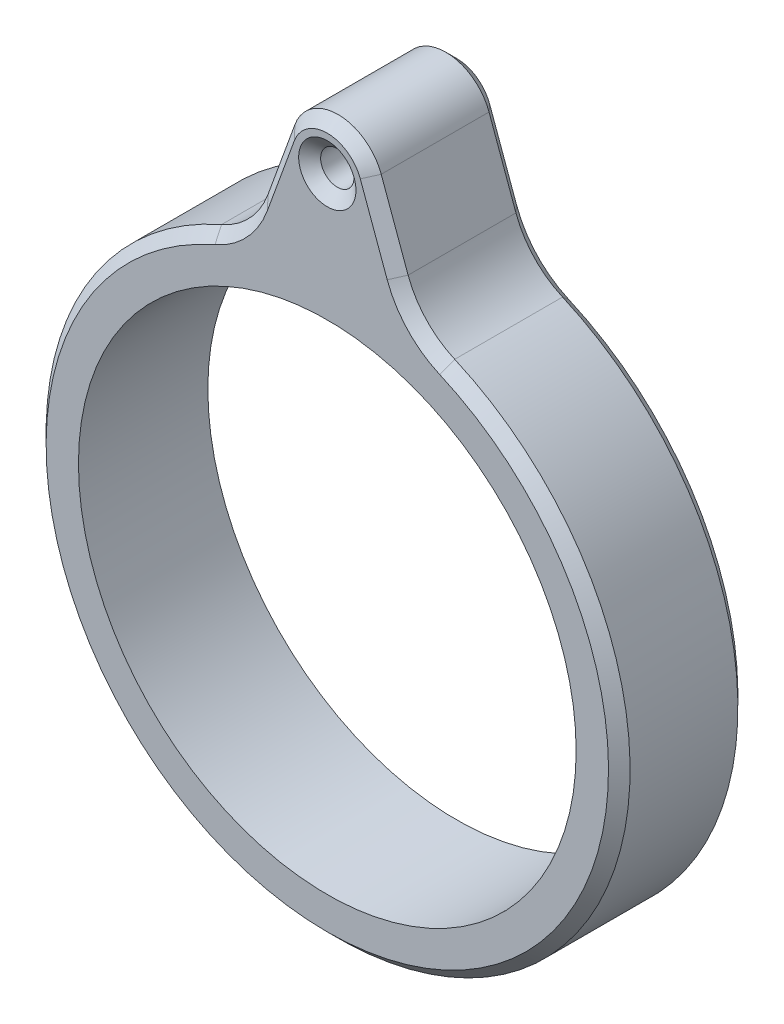
SolidWorks part; units mm, degrees
material "PET"
ref_plane "Front Plane" through (0, 0, 0) normal (0, 0, 1) x (1, 0, 0)
ref_plane "Top Plane" through (0, 0, 0) normal (0, 1, 0) x (1, 0, 0)
ref_plane "Right Plane" through (0, 0, 0) normal (1, 0, 0) x (0, 0, -1)
sketch "Sketch1" plane through (0, 0, 0) normal (0, 0, 1) x (1, 0, 0)
  circle A0 centre (0, 0) radius 36.6395
  circle A1 centre (0, 0) radius 42.9895
  dimension "D1" = 73.279
  dimension "D2" = 6.35
extrude "Boss-Extrude1" add sketch "Sketch1" along normal blind 19.05
sketch "Sketch3" plane through (0, 0, 19.05) normal (0, 0, 1) x (1, 0, 0)
  line L0 (0, 42.9895) -> (0, 57.5932) construction
  line L1 (0, -10.4775) -> (0, 10.4775) construction
  line L2 (0, 57.5932) -> (-6.35, 57.5932) construction
  line L3 (-6.35, 57.5932) -> (-12.3218, 41.1858)
  line L4 (0, 62.0395) -> (0, 57.5932) construction
  line L5 (6.35, 57.5932) -> (12.3218, 41.1858)
  circle A0 centre (0, 0) radius 42.9895 construction
  arc A1 (-12.3218, 41.1858) -> (12.3218, 41.1858) centre (0, -1.5668) cw
  arc A2 (-6.35, 57.5932) -> (0, 62.0395) centre (0, 55.282) cw
  arc A3 (6.35, 57.5932) -> (0, 62.0395) centre (0, 55.282) ccw
  point P15 (0, 0)
  point P16 (0, 0)
  point P17 (0, 42.9895)
  dimension "D1" = 20
  dimension "D2" = 6.35
  dimension "D3" = 63.6063
  dimension "D4" = 19.05
extrude "Boss-Extrude2" add sketch "Sketch3" against normal through all
fillet "Fillet1" radius 12.7 2 edges at (12.3218, 41.1858, 9.525) (-12.3218, 41.1858, 9.525)
chamfer "Chamfer1" distance 1.5875 angle 45 12 edges at (0, 62.0395, 19.05) (0, 62.0395, 0) (-8.3306, 52.1516, 0) (-8.3306, 52.1516, 19.05) (8.3306, 52.1516, 19.05) (8.3306, 52.1516, 0) (-12.9916, 42.3553, 0) (12.9916, 42.3553, 0) (0, -42.9895, 0) (-12.9916, 42.3553, 19.05) (12.9916, 42.3553, 19.05) (0, -42.9895, 19.05)
hole_wizard "CSK for #8 Flat Head Machine Screw (100)1" positions "Sketch4" profile "Sketch5" countersink size "#8" standard "ANSI Inch" end condition through all
sketch "Sketch4" plane through (0, 0, 19.05) normal (0, 0, 1) x (1, 0, 0)
  point P0 (0, 55.282)
sketch "Sketch5" plane through (0, 55.282, 19.05) normal (1, 0, 0) x (0, -1, 0)
  line L0 (0, 0) -> (0, 19.05)
  line L1 (0, 19.05) -> (2.4574, 19.05)
  line L2 (2.4574, 19.05) -> (2.4574, 1.4759)
  line L3 (2.4574, 1.4759) -> (4.2164, 0)
  line L5 (4.2164, 0) -> (0, 0)
  line L6 (-2.4574, 1.4759) -> (-4.2164, 0) construction
  line L11 (0, -6.35) -> (0, 107.95) construction
  dimension "Thru Hole Dia." = 4.9149
  dimension "Thru Hole Depth" = 19.05
  dimension "Near C'Sink Dia." = 8.4328
  dimension "Near C'Sink Angle" = 100
